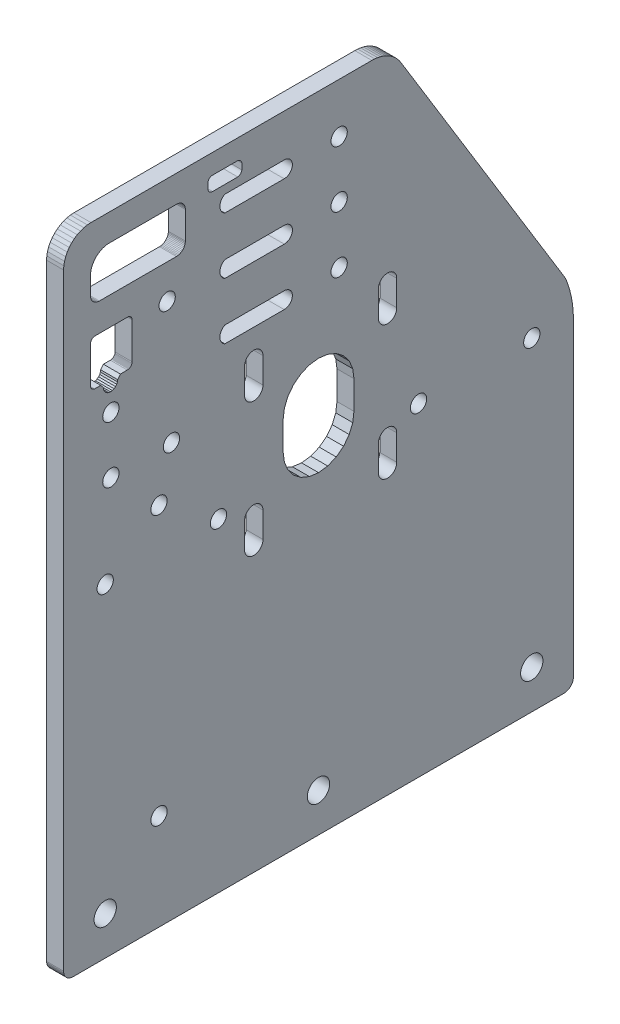
SolidWorks part; units mm, degrees
ref_plane "Front Plane" through (0, 0, 0) normal (0, 0, 1) x (1, 0, 0)
ref_plane "Top Plane" through (0, 0, 0) normal (0, 1, 0) x (1, 0, 0)
ref_plane "Right Plane" through (0, 0, 0) normal (1, 0, 0) x (0, 0, -1)
ref_plane "Plane1" through (0, 0, 0) normal (-1, 0, 0) x (0, -1, 0)
sketch "Sketch1" plane through (0, 0, 0) normal (-1, 0, 0) x (0, -1, 0)
  line L0 (-590.2121, -1614.2437) -> (-495.2304, -1672.3356)
  line L1 (-495.2304, -1672.3356) -> (-492.9855, -1673.1988)
  line L2 (-492.9855, -1673.1988) -> (-490.6881, -1673.9103)
  line L3 (-490.6881, -1673.9103) -> (-488.3483, -1674.4671)
  line L4 (-488.3483, -1674.4671) -> (-485.9766, -1674.8665)
  line L5 (-485.9766, -1674.8665) -> (-483.5835, -1675.1069)
  line L6 (-483.5835, -1675.1069) -> (-481.1798, -1675.1871)
  line L7 (-481.1798, -1675.1871) -> (-371.8266, -1675.1871)
  line L8 (-371.8266, -1675.1871) -> (-371.3877, -1675.1584)
  line L9 (-371.3877, -1675.1584) -> (-370.9562, -1675.0725)
  line L10 (-370.9562, -1675.0725) -> (-370.5397, -1674.9312)
  line L11 (-370.5397, -1674.9312) -> (-370.1452, -1674.7366)
  line L12 (-370.1452, -1674.7366) -> (-369.7795, -1674.4922)
  line L13 (-369.7795, -1674.4922) -> (-369.4487, -1674.2022)
  line L14 (-369.4487, -1674.2022) -> (-369.1587, -1673.8715)
  line L15 (-369.1587, -1673.8715) -> (-368.9143, -1673.5057)
  line L16 (-368.9143, -1673.5057) -> (-368.7198, -1673.1112)
  line L17 (-368.7198, -1673.1112) -> (-368.5784, -1672.6947)
  line L18 (-368.5784, -1672.6947) -> (-368.4926, -1672.2633)
  line L19 (-368.4926, -1672.2633) -> (-368.4638, -1671.8243)
  line L20 (-368.4638, -1671.8243) -> (-368.4638, -1498.5099)
  line L21 (-368.4638, -1498.5099) -> (-368.4926, -1498.071)
  line L22 (-368.4926, -1498.071) -> (-368.5784, -1497.6396)
  line L23 (-368.5784, -1497.6396) -> (-368.7198, -1497.223)
  line L24 (-368.7198, -1497.223) -> (-368.9143, -1496.8285)
  line L25 (-368.9143, -1496.8285) -> (-369.1587, -1496.4628)
  line L26 (-369.1587, -1496.4628) -> (-369.4487, -1496.1321)
  line L27 (-369.4487, -1496.1321) -> (-369.7795, -1495.842)
  line L28 (-369.7795, -1495.842) -> (-370.1452, -1495.5977)
  line L29 (-370.1452, -1495.5977) -> (-370.5397, -1495.4031)
  line L30 (-370.5397, -1495.4031) -> (-370.9562, -1495.2617)
  line L31 (-370.9562, -1495.2617) -> (-371.3877, -1495.1759)
  line L32 (-371.3877, -1495.1759) -> (-371.8266, -1495.1471)
  line L33 (-371.8266, -1495.1471) -> (-586.2881, -1495.1456)
  line L34 (-586.2881, -1495.1456) -> (-587.5497, -1495.2283)
  line L35 (-587.5497, -1495.2283) -> (-588.7897, -1495.475)
  line L36 (-588.7897, -1495.475) -> (-589.987, -1495.8813)
  line L37 (-589.987, -1495.8813) -> (-591.1209, -1496.4405)
  line L38 (-591.1209, -1496.4405) -> (-592.1721, -1497.1429)
  line L39 (-592.1721, -1497.1429) -> (-593.1227, -1497.9766)
  line L40 (-593.1227, -1497.9766) -> (-593.9563, -1498.9271)
  line L41 (-593.9563, -1498.9271) -> (-594.6588, -1499.9784)
  line L42 (-594.6588, -1499.9784) -> (-595.218, -1501.1123)
  line L43 (-595.218, -1501.1123) -> (-595.6244, -1502.3095)
  line L44 (-595.6244, -1502.3095) -> (-595.871, -1503.5495)
  line L45 (-595.871, -1503.5495) -> (-595.9537, -1504.8111)
  line L46 (-595.9537, -1504.8111) -> (-595.9537, -1603.9943)
  line L47 (-595.9537, -1603.9943) -> (-595.9102, -1605.016)
  line L48 (-595.9102, -1605.016) -> (-595.78, -1606.0302)
  line L49 (-595.78, -1606.0302) -> (-595.5641, -1607.0297)
  line L50 (-595.5641, -1607.0297) -> (-595.264, -1608.0073)
  line L51 (-595.264, -1608.0073) -> (-594.8819, -1608.9558)
  line L52 (-594.8819, -1608.9558) -> (-594.4205, -1609.8683)
  line L53 (-594.4205, -1609.8683) -> (-593.8833, -1610.7384)
  line L54 (-593.8833, -1610.7384) -> (-593.274, -1611.5596)
  line L55 (-593.274, -1611.5596) -> (-592.5971, -1612.3261)
  line L56 (-592.5971, -1612.3261) -> (-591.8575, -1613.0323)
  line L57 (-591.8575, -1613.0323) -> (-591.0606, -1613.673)
  line L58 (-591.0606, -1613.673) -> (-590.2121, -1614.2437)
  line L59 (-575.2278, -1552.0779) -> (-575.2278, -1573.0506)
  line L60 (-580.9777, -1573.098) -> (-580.9777, -1552.0841)
  line L61 (-535.2278, -1552.0792) -> (-535.2278, -1573.052)
  line L62 (-540.9777, -1573.0993) -> (-540.9777, -1552.0854)
  line L63 (-555.2276, -1552.095) -> (-555.2276, -1573.0814)
  line L64 (-560.9776, -1573.1131) -> (-560.9776, -1552.0992)
  line L65 (-524.9137, -1559.0552) -> (-515.9137, -1559.0552)
  line L66 (-515.9137, -1565.5552) -> (-524.9137, -1565.5552)
  line L67 (-524.9137, -1606.2991) -> (-515.9137, -1606.2991)
  line L68 (-515.9137, -1612.7991) -> (-524.9137, -1612.7991)
  line L69 (-477.6698, -1606.2991) -> (-468.6699, -1606.2991)
  line L70 (-468.6699, -1612.7991) -> (-477.6698, -1612.7991)
  line L71 (-477.6698, -1559.0528) -> (-468.6695, -1559.0552)
  line L72 (-468.6712, -1565.5552) -> (-477.6698, -1565.5528)
  line L73 (-586.0336, -1536.5791) -> (-586.215, -1536.2112)
  line L74 (-586.215, -1536.2112) -> (-586.3468, -1535.8228)
  line L75 (-586.3468, -1535.8228) -> (-586.4269, -1535.4204)
  line L76 (-586.4269, -1535.4204) -> (-586.4537, -1535.0111)
  line L77 (-586.4537, -1535.0111) -> (-586.4537, -1511.2962)
  line L78 (-586.4537, -1511.2962) -> (-586.3968, -1510.4284)
  line L79 (-586.3968, -1510.4284) -> (-586.2271, -1509.5753)
  line L80 (-586.2271, -1509.5753) -> (-585.9476, -1508.7517)
  line L81 (-585.9476, -1508.7517) -> (-585.5629, -1507.9717)
  line L82 (-585.5629, -1507.9717) -> (-585.0797, -1507.2485)
  line L83 (-585.0797, -1507.2485) -> (-584.5062, -1506.5946)
  line L84 (-584.5062, -1506.5946) -> (-583.8523, -1506.0211)
  line L85 (-583.8523, -1506.0211) -> (-583.1291, -1505.5379)
  line L86 (-583.1291, -1505.5379) -> (-582.3491, -1505.1533)
  line L87 (-582.3491, -1505.1533) -> (-581.5255, -1504.8737)
  line L88 (-581.5255, -1504.8737) -> (-580.6725, -1504.704)
  line L89 (-580.6725, -1504.704) -> (-579.8046, -1504.6471)
  line L90 (-579.8046, -1504.6471) -> (-573.6169, -1504.6471)
  line L91 (-573.6169, -1504.6471) -> (-573.2076, -1504.6739)
  line L92 (-573.2076, -1504.6739) -> (-572.8052, -1504.754)
  line L93 (-572.8052, -1504.754) -> (-572.4168, -1504.8858)
  line L94 (-572.4168, -1504.8858) -> (-572.0489, -1505.0673)
  line L95 (-572.0489, -1505.0673) -> (-571.7078, -1505.2952)
  line L96 (-571.7078, -1505.2952) -> (-571.3994, -1505.5656)
  line L97 (-571.3994, -1505.5656) -> (-571.1289, -1505.8741)
  line L98 (-571.1289, -1505.8741) -> (-570.901, -1506.2151)
  line L99 (-570.901, -1506.2151) -> (-570.7196, -1506.583)
  line L100 (-570.7196, -1506.583) -> (-570.5877, -1506.9715)
  line L101 (-570.5877, -1506.9715) -> (-570.5077, -1507.3738)
  line L102 (-570.5077, -1507.3738) -> (-570.4809, -1507.7831)
  line L103 (-570.4809, -1507.7831) -> (-570.4809, -1535.0111)
  line L104 (-570.4809, -1535.0111) -> (-570.5077, -1535.4204)
  line L105 (-570.5077, -1535.4204) -> (-570.5877, -1535.8228)
  line L106 (-570.5877, -1535.8228) -> (-570.7196, -1536.2112)
  line L107 (-570.7196, -1536.2112) -> (-570.901, -1536.5791)
  line L108 (-570.901, -1536.5791) -> (-571.1289, -1536.9202)
  line L109 (-571.1289, -1536.9202) -> (-571.3994, -1537.2286)
  line L110 (-571.3994, -1537.2286) -> (-571.7078, -1537.4991)
  line L111 (-571.7078, -1537.4991) -> (-572.0489, -1537.727)
  line L112 (-572.0489, -1537.727) -> (-572.4168, -1537.9084)
  line L113 (-572.4168, -1537.9084) -> (-572.8052, -1538.0403)
  line L114 (-572.8052, -1538.0403) -> (-573.2076, -1538.1203)
  line L115 (-573.2076, -1538.1203) -> (-573.6169, -1538.1471)
  line L116 (-573.6169, -1538.1471) -> (-583.3177, -1538.1471)
  line L117 (-583.3177, -1538.1471) -> (-583.727, -1538.1203)
  line L118 (-583.727, -1538.1203) -> (-584.1293, -1538.0403)
  line L119 (-584.1293, -1538.0403) -> (-584.5178, -1537.9084)
  line L120 (-584.5178, -1537.9084) -> (-584.8857, -1537.727)
  line L121 (-584.8857, -1537.727) -> (-585.2268, -1537.4991)
  line L122 (-585.2268, -1537.4991) -> (-585.5352, -1537.2286)
  line L123 (-585.5352, -1537.2286) -> (-585.8057, -1536.9202)
  line L124 (-585.8057, -1536.9202) -> (-586.0336, -1536.5791)
  line L125 (-560.5397, -1505.8783) -> (-560.4696, -1505.6715)
  line L126 (-560.4696, -1505.6715) -> (-560.373, -1505.4757)
  line L127 (-560.373, -1505.4757) -> (-560.2517, -1505.2942)
  line L128 (-560.2517, -1505.2942) -> (-560.1078, -1505.1301)
  line L129 (-560.1078, -1505.1301) -> (-559.9436, -1504.9862)
  line L130 (-559.9436, -1504.9862) -> (-559.7621, -1504.8649)
  line L131 (-559.7621, -1504.8649) -> (-559.5663, -1504.7683)
  line L132 (-559.5663, -1504.7683) -> (-559.3596, -1504.6981)
  line L133 (-559.3596, -1504.6981) -> (-559.1312, -1504.6471)
  line L134 (-559.1312, -1504.6471) -> (-558.9276, -1504.6413)
  line L135 (-558.9276, -1504.6413) -> (-548.4809, -1504.6452)
  line L136 (-548.4809, -1504.6452) -> (-545.8818, -1504.6452)
  line L137 (-545.8818, -1504.6452) -> (-545.6677, -1504.6877)
  line L138 (-545.6677, -1504.6877) -> (-545.461, -1504.7579)
  line L139 (-545.461, -1504.7579) -> (-545.2652, -1504.8545)
  line L140 (-545.2652, -1504.8545) -> (-545.0837, -1504.9758)
  line L141 (-545.0837, -1504.9758) -> (-544.9196, -1505.1197)
  line L142 (-544.9196, -1505.1197) -> (-544.7756, -1505.2838)
  line L143 (-544.7756, -1505.2838) -> (-544.6543, -1505.4654)
  line L144 (-544.6543, -1505.4654) -> (-544.5578, -1505.6612)
  line L145 (-544.5578, -1505.6612) -> (-544.4876, -1505.8679)
  line L146 (-544.4876, -1505.8679) -> (-544.445, -1506.082)
  line L147 (-544.445, -1506.082) -> (-544.4414, -1508.2677)
  line L148 (-544.4414, -1508.2677) -> (-543.221, -1509.2377)
  line L149 (-543.221, -1509.2377) -> (-542.574, -1509.3226)
  line L150 (-542.574, -1509.3226) -> (-541.9709, -1509.5721)
  line L151 (-541.9709, -1509.5721) -> (-541.453, -1509.9692)
  line L152 (-541.453, -1509.9692) -> (-541.0555, -1510.4868)
  line L153 (-541.0555, -1510.4868) -> (-540.8055, -1511.0897)
  line L154 (-540.8055, -1511.0897) -> (-540.72, -1511.7367)
  line L155 (-540.72, -1511.7367) -> (-540.805, -1512.3838)
  line L156 (-540.805, -1512.3838) -> (-541.0545, -1512.9868)
  line L157 (-541.0545, -1512.9868) -> (-541.4516, -1513.5047)
  line L158 (-541.4516, -1513.5047) -> (-541.9692, -1513.9022)
  line L159 (-541.9692, -1513.9022) -> (-542.572, -1514.1522)
  line L160 (-542.572, -1514.1522) -> (-543.219, -1514.2377)
  line L161 (-543.219, -1514.2377) -> (-544.4323, -1515.2077)
  line L162 (-544.4323, -1515.2077) -> (-544.4307, -1517.6776)
  line L163 (-544.4307, -1517.6776) -> (-544.4876, -1518.1096)
  line L164 (-544.4876, -1518.1096) -> (-544.5578, -1518.3163)
  line L165 (-544.5578, -1518.3163) -> (-544.6543, -1518.5121)
  line L166 (-544.6543, -1518.5121) -> (-544.7756, -1518.6936)
  line L167 (-544.7756, -1518.6936) -> (-544.9196, -1518.8578)
  line L168 (-544.9196, -1518.8578) -> (-545.0837, -1519.0017)
  line L169 (-545.0837, -1519.0017) -> (-545.2652, -1519.123)
  line L170 (-545.2652, -1519.123) -> (-545.461, -1519.2196)
  line L171 (-545.461, -1519.2196) -> (-545.6677, -1519.2897)
  line L172 (-545.6677, -1519.2897) -> (-546.0997, -1519.3486)
  line L173 (-546.0997, -1519.3486) -> (-558.9578, -1519.3427)
  line L174 (-558.9578, -1519.3427) -> (-559.1455, -1519.3427)
  line L175 (-559.1455, -1519.3427) -> (-559.3596, -1519.3001)
  line L176 (-559.3596, -1519.3001) -> (-559.5663, -1519.23)
  line L177 (-559.5663, -1519.23) -> (-559.7621, -1519.1334)
  line L178 (-559.7621, -1519.1334) -> (-559.9436, -1519.0121)
  line L179 (-559.9436, -1519.0121) -> (-560.1078, -1518.8682)
  line L180 (-560.1078, -1518.8682) -> (-560.2517, -1518.704)
  line L181 (-560.2517, -1518.704) -> (-560.373, -1518.5225)
  line L182 (-560.373, -1518.5225) -> (-560.4696, -1518.3267)
  line L183 (-560.4696, -1518.3267) -> (-560.5397, -1518.12)
  line L184 (-560.5397, -1518.12) -> (-560.5823, -1517.9059)
  line L185 (-560.5823, -1517.9059) -> (-560.5823, -1517.6796)
  line L186 (-560.5823, -1517.6796) -> (-560.568, -1506.084)
  line L187 (-560.568, -1506.084) -> (-560.5397, -1505.8783)
  line L188 (-512.6093, -1578.9371) -> (-510.6228, -1576.3483)
  line L189 (-510.6228, -1576.3483) -> (-508.034, -1574.3618)
  line L190 (-508.034, -1574.3618) -> (-505.0192, -1573.1131)
  line L191 (-505.0192, -1573.1131) -> (-501.784, -1572.6871)
  line L192 (-501.784, -1572.6871) -> (-491.784, -1572.6871)
  line L193 (-491.784, -1572.6871) -> (-488.5487, -1573.1131)
  line L194 (-488.5487, -1573.1131) -> (-485.534, -1574.3618)
  line L195 (-485.534, -1574.3618) -> (-482.9451, -1576.3483)
  line L196 (-482.9451, -1576.3483) -> (-480.9587, -1578.9371)
  line L197 (-480.9587, -1578.9371) -> (-479.7099, -1581.9519)
  line L198 (-479.7099, -1581.9519) -> (-479.284, -1585.1871)
  line L199 (-479.284, -1585.1871) -> (-479.7099, -1588.4224)
  line L200 (-479.7099, -1588.4224) -> (-480.9587, -1591.4371)
  line L201 (-480.9587, -1591.4371) -> (-482.9451, -1594.026)
  line L202 (-482.9451, -1594.026) -> (-485.534, -1596.0125)
  line L203 (-485.534, -1596.0125) -> (-488.5487, -1597.2612)
  line L204 (-488.5487, -1597.2612) -> (-491.784, -1597.6871)
  line L205 (-491.784, -1597.6871) -> (-501.784, -1597.6871)
  line L206 (-501.784, -1597.6871) -> (-505.0192, -1597.2612)
  line L207 (-505.0192, -1597.2612) -> (-508.034, -1596.0125)
  line L208 (-508.034, -1596.0125) -> (-510.6228, -1594.026)
  line L209 (-510.6228, -1594.026) -> (-512.6093, -1591.4371)
  line L210 (-512.6093, -1591.4371) -> (-513.858, -1588.4224)
  line L211 (-513.858, -1588.4224) -> (-514.284, -1585.1871)
  line L212 (-514.284, -1585.1871) -> (-513.858, -1581.9519)
  line L213 (-513.858, -1581.9519) -> (-512.6093, -1578.9371)
  line L214 (-588.9809, -1556.6482) -> (-588.9809, -1547.5504)
  line L215 (-587.544, -1546.1136) -> (-585.6436, -1546.0993)
  line L216 (-583.9746, -1547.7683) -> (-583.9889, -1556.6482)
  line L217 (-585.4257, -1558.085) -> (-587.544, -1558.085)
  arc A0 (-580.9777, -1552.0841) -> (-575.2278, -1552.0779) centre (-578.1011, -1553.5965) cw
  arc A1 (-575.2278, -1573.0506) -> (-580.9777, -1573.098) centre (-578.1027, -1573.0743) cw
  arc A2 (-540.9777, -1552.0854) -> (-535.2278, -1552.0792) centre (-538.1011, -1553.5978) cw
  arc A3 (-535.2278, -1573.052) -> (-540.9777, -1573.0993) centre (-538.1028, -1573.0757) cw
  arc A4 (-560.9776, -1552.0992) -> (-555.2276, -1552.095) centre (-558.1015, -1553.6126) cw
  arc A5 (-555.2276, -1573.0814) -> (-560.9776, -1573.1131) centre (-558.1026, -1573.0972) cw
  arc A6 (-515.9137, -1559.0552) -> (-515.9137, -1565.5552) centre (-515.9137, -1562.3052) cw
  arc A7 (-524.9137, -1565.5552) -> (-524.9137, -1559.0552) centre (-524.9137, -1562.3052) cw
  arc A8 (-515.9137, -1606.2991) -> (-515.9137, -1612.7991) centre (-515.9137, -1609.5491) cw
  arc A9 (-524.9137, -1612.7991) -> (-524.9137, -1606.2991) centre (-524.9137, -1609.5491) cw
  arc A10 (-468.6699, -1606.2991) -> (-468.6699, -1612.7991) centre (-468.6699, -1609.5491) cw
  arc A11 (-477.6698, -1612.7991) -> (-477.6698, -1606.2991) centre (-477.6698, -1609.5491) cw
  arc A12 (-468.6695, -1559.0552) -> (-468.6712, -1565.5552) centre (-468.6703, -1562.3052) cw
  arc A13 (-477.6698, -1565.5528) -> (-477.6698, -1559.0528) centre (-477.669, -1562.3028) cw
  circle A14 centre (-382.1591, -1509.8471) radius 3.9435
  circle A15 centre (-382.1591, -1585.1671) radius 3.9435
  circle A16 centre (-382.1591, -1660.4871) radius 3.9435
  circle A17 centre (-538.3993, -1592.4578) radius 2.875
  circle A18 centre (-558.4485, -1592.4578) radius 2.875
  circle A19 centre (-578.4485, -1592.4578) radius 2.875
  circle A20 centre (-534.4436, -1511.8471) radius 2.875
  circle A21 centre (-558.4024, -1531.723) radius 2.875
  circle A22 centre (-514.4436, -1511.8471) radius 2.875
  circle A23 centre (-514.4436, -1533.239) radius 2.875
  circle A24 centre (-497.4962, -1528.8471) radius 2.875
  circle A25 centre (-482.7991, -1549.8471) radius 2.875
  circle A26 centre (-482.7991, -1509.8471) radius 2.875
  circle A27 centre (-482.7991, -1620.4871) radius 2.875
  circle A28 centre (-482.7991, -1660.4871) radius 2.875
  circle A29 centre (-402.4962, -1528.8471) radius 2.875
  arc A30 (-588.9809, -1547.5504) -> (-587.544, -1546.1136) centre (-587.3137, -1547.7807) cw
  arc A31 (-585.6436, -1546.0993) -> (-583.9746, -1547.7683) centre (-585.6436, -1547.7683) cw
  arc A32 (-583.9889, -1556.6482) -> (-585.4257, -1558.085) centre (-585.656, -1556.4179) cw
  arc A33 (-587.544, -1558.085) -> (-588.9809, -1556.6482) centre (-587.3262, -1556.4303) cw
  dimension "D1" = 7.887
  dimension "D2" = 5.75
  dimension "D3" = 5.75
  dimension "D4" = 3.25
  dimension "D5" = 5.75
  dimension "D6" = 5.75
  dimension "D7" = 2.875
  dimension "D8" = 5.75
  dimension "D9" = 5.75
extrude "Boss-Extrude1" add sketch "Sketch1" against normal blind 6
equation "\"holeMOD\"= 0.75mm"
equation "\"D1@Sketch1\"=7.137mm + \"holeMOD\""
equation "\"D2@Sketch1\"=5.00mm + \"holeMOD\""
equation "\"D3@Sketch1\"=5.00mm + \"holeMOD\""
equation "\"D4@Sketch1\"=2.50mm + \"holeMOD\""
equation "\"D5@Sketch1\"=5.00mm + \"holeMOD\""
equation "\"D6@Sketch1\"=5.00mm + \"holeMOD\""
equation "\"D7@Sketch1\"=2.50004757mm + \"holeMOD\"/2"
equation "\"D8@Sketch1\"=5.00mm + \"holeMOD\""
equation "\"D9@Sketch1\"=5.00mm + \"holeMOD\""
